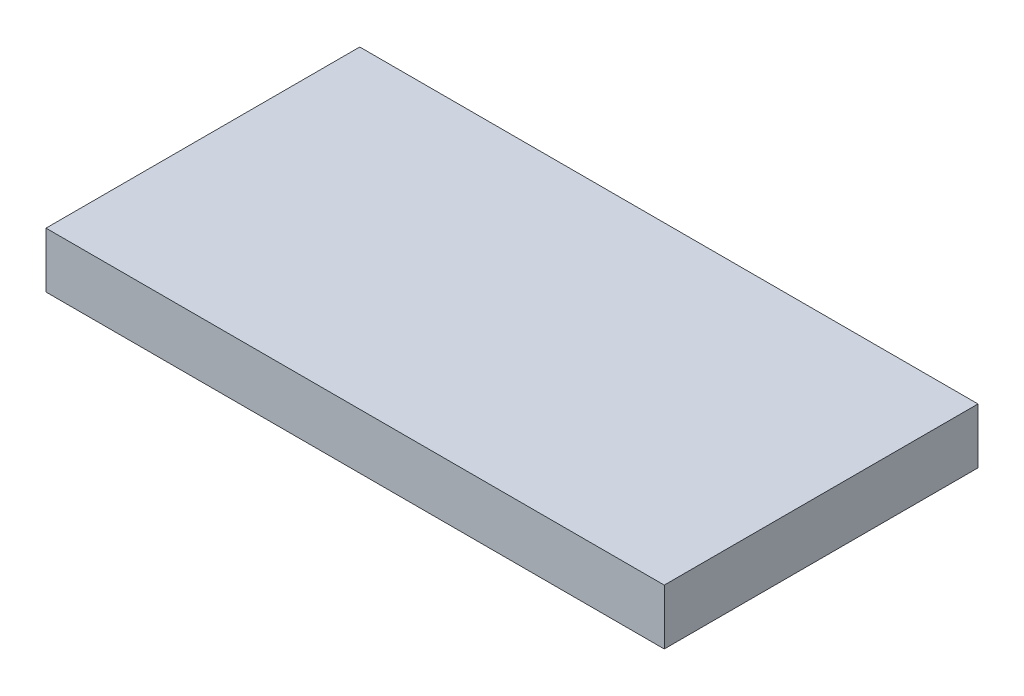
SolidWorks part; units mm, degrees
ref_plane "Front" through (0, 0, 0) normal (0, 0, 1) x (1, 0, 0)
ref_plane "Top" through (0, 0, 0) normal (0, 1, 0) x (1, 0, 0)
ref_plane "Right" through (0, 0, 0) normal (1, 0, 0) x (0, 0, -1)
sketch "Sketch1" plane through (0, 0, 0) normal (0, 1, 0) x (1, 0, 0)
  line L1 (0, 0) -> (67, 0)
  line L2 (0, 0) -> (0, 34)
  line L3 (0, 34) -> (67, 34)
  line L4 (67, 0) -> (67, 34)
  dimension "D1" = 67
  dimension "D2" = 34
extrude "Boss-Extrude1" add sketch "Sketch1" along normal blind 6
